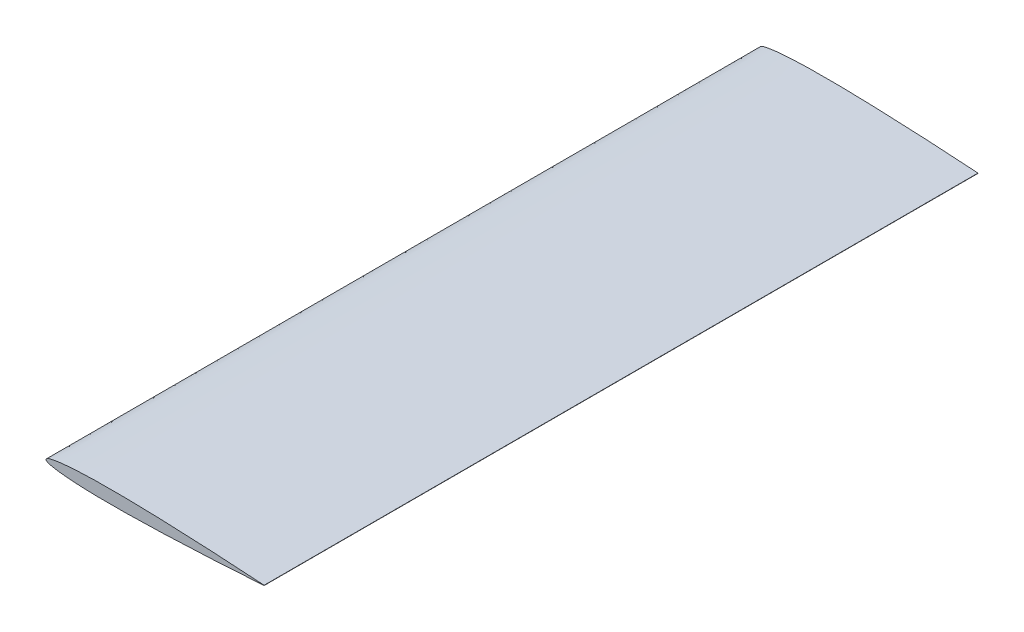
SolidWorks part; units mm, degrees
ref_plane "Front Plane" through (0, 0, 0) normal (0, 0, 1) x (1, 0, 0)
ref_plane "Top Plane" through (0, 0, 0) normal (0, 1, 0) x (1, 0, 0)
ref_plane "Right Plane" through (0, 0, 0) normal (1, 0, 0) x (0, 0, -1)
curve "Curve1"
  spline degree 3 poles (25.4, 0.016, 0) (24.9767, 0.0451, 0) (24.1302, 0.1034, 0) (22.437, 0.2117, 0) (20.3205, 0.3361, 0) (17.7804, 0.4681, 0) (15.2404, 0.5832, 0) (12.7004, 0.6768, 0) (10.1604, 0.7436, 0) (8.0434, 0.7669, 0) (6.3499, 0.7577, 0) (5.0797, 0.7326, 0) (3.8089, 0.6843, 0) (2.7512, 0.6171, 0) (1.9027, 0.5359, 0) (1.272, 0.4592, 0) (0.7223, 0.3537, 0) (0.3193, 0.2604, 0) (-0.1745, 0, 0) (0.3193, -0.2604, 0) (0.7223, -0.3537, 0) (1.272, -0.4592, 0) (1.9027, -0.5359, 0) (2.7512, -0.6171, 0) (3.8089, -0.6843, 0) (5.0797, -0.7326, 0) (6.3499, -0.7577, 0) (8.0434, -0.7669, 0) (10.1604, -0.7436, 0) (12.7004, -0.6768, 0) (15.2404, -0.5832, 0) (17.7804, -0.4681, 0) (20.3205, -0.3361, 0) (22.437, -0.2117, 0) (24.1302, -0.1034, 0) (24.9767, -0.0451, 0) (25.4, -0.016, 0) knots 0 0 0 0 0.024925 0.049843 0.099663 0.149465 0.199249 0.249016 0.298767 0.348504 0.373371 0.398243 0.42313 0.448052 0.460543 0.47308 0.485731 0.492201 0.5 0.507799 0.514269 0.52692 0.539457 0.551948 0.57687 0.601757 0.626629 0.651496 0.701233 0.750984 0.800751 0.850535 0.900337 0.950157 0.975075 1 1 1 1
sketch "Sketch1" plane through (0, 0, 0) normal (0, 0, 1) x (1, 0, 0)
  line L0 (2.7618, -8.6494) -> (2.7618, -9.1775)
  line L1 (2.7618, -8.9135) -> (-416.3382, -8.9135) construction
  spline S1 degree 3 poles (2.7618, -8.6494) (-4.2229, -8.1688) (-18.1904, -7.2078) (-46.128, -5.4206) (-81.0504, -3.3678) (-122.9612, -1.1891) (-164.8709, 0.709) (-206.7811, 2.2537) (-248.6921, 3.3554) (-283.6224, 3.7401) (-311.5654, 3.5879) (-332.5229, 3.1742) (-353.4913, 2.3771) (-370.9432, 1.2692) (-384.9443, -0.0718) (-395.3504, -1.3361) (-404.4204, -3.0773) (-411.0693, -4.6175) (-419.2182, -8.9135) (-411.0693, -13.2094) (-404.4204, -14.7496) (-395.3504, -16.4909) (-384.9443, -17.7552) (-370.9432, -19.0961) (-353.4913, -20.204) (-332.5229, -21.0012) (-311.5654, -21.4148) (-283.6224, -21.5671) (-248.6921, -21.1823) (-206.7811, -20.0807) (-164.8709, -18.5359) (-122.9612, -16.6378) (-81.0504, -14.4591) (-46.128, -12.4064) (-18.1904, -10.6191) (-4.2229, -9.6581) (2.7618, -9.1775) knots 0 0 0 0 0.024925 0.049843 0.099663 0.149465 0.199249 0.249016 0.298767 0.348504 0.373371 0.398243 0.42313 0.448052 0.460543 0.47308 0.485731 0.492201 0.5 0.507799 0.514269 0.52692 0.539457 0.551948 0.57687 0.601757 0.626629 0.651496 0.701233 0.750984 0.800751 0.850535 0.900337 0.950157 0.975075 1 1 1 1
  point P4 (0, 0)
  point P5 (0, 0)
  point P6 (0, 0)
  point P7 (-1.372, -0.2891)
  point P8 (0, 0)
  point P9 (2.7618, -0.1259)
  dimension "D1" = 419.1
extrude "Boss-Extrude1" add sketch "Sketch1" along normal blind 1371.6
sketch "Sketch2" plane through (0, 0, 1371.6) normal (0, 0, 1) x (1, 0, 0)
  line L0 (2.7618, -8.9135) -> (-416.3382, -8.9135) construction
  line L1 (2.7618, -9.1775) -> (2.7618, -8.6494) construction
  line L2 (-416.3382, -8.9135) -> (-416.3382, 28.1757) construction
  line L3 (2.7618, -8.9135) -> (2.7618, 8.0306) construction
  spline S1 degree 3 poles (2.7618, -8.6494) (-4.2229, -8.1688) (-18.1904, -7.2078) (-46.128, -5.4206) (-81.0504, -3.3678) (-122.9612, -1.1891) (-164.8709, 0.709) (-206.7811, 2.2537) (-248.6921, 3.3554) (-283.6224, 3.7401) (-311.5654, 3.5879) (-332.5229, 3.1742) (-353.4913, 2.3771) (-370.9432, 1.2692) (-384.9443, -0.0718) (-395.3504, -1.3361) (-404.4204, -3.0773) (-411.0693, -4.6175) (-419.2182, -8.9135) (-411.0693, -13.2094) (-404.4204, -14.7496) (-395.3504, -16.4909) (-384.9443, -17.7552) (-370.9432, -19.0961) (-353.4913, -20.204) (-332.5229, -21.0012) (-311.5654, -21.4148) (-283.6224, -21.5671) (-248.6921, -21.1823) (-206.7811, -20.0807) (-164.8709, -18.5359) (-122.9612, -16.6378) (-81.0504, -14.4591) (-46.128, -12.4064) (-18.1904, -10.6191) (-4.2229, -9.6581) (2.7618, -9.1775) knots 0 0 0 0 0.024925 0.049843 0.099663 0.149465 0.199249 0.249016 0.298767 0.348504 0.373371 0.398243 0.42313 0.448052 0.460543 0.47308 0.485731 0.492201 0.5 0.507799 0.514269 0.52692 0.539457 0.551948 0.57687 0.601757 0.626629 0.651496 0.701233 0.750984 0.800751 0.850535 0.900337 0.950157 0.975075 1 1 1 1 construction
  point P4 (0, 0)
  point P12 (2.7618, -8.9141)
  point P13 (2.7618, 8.0306)
